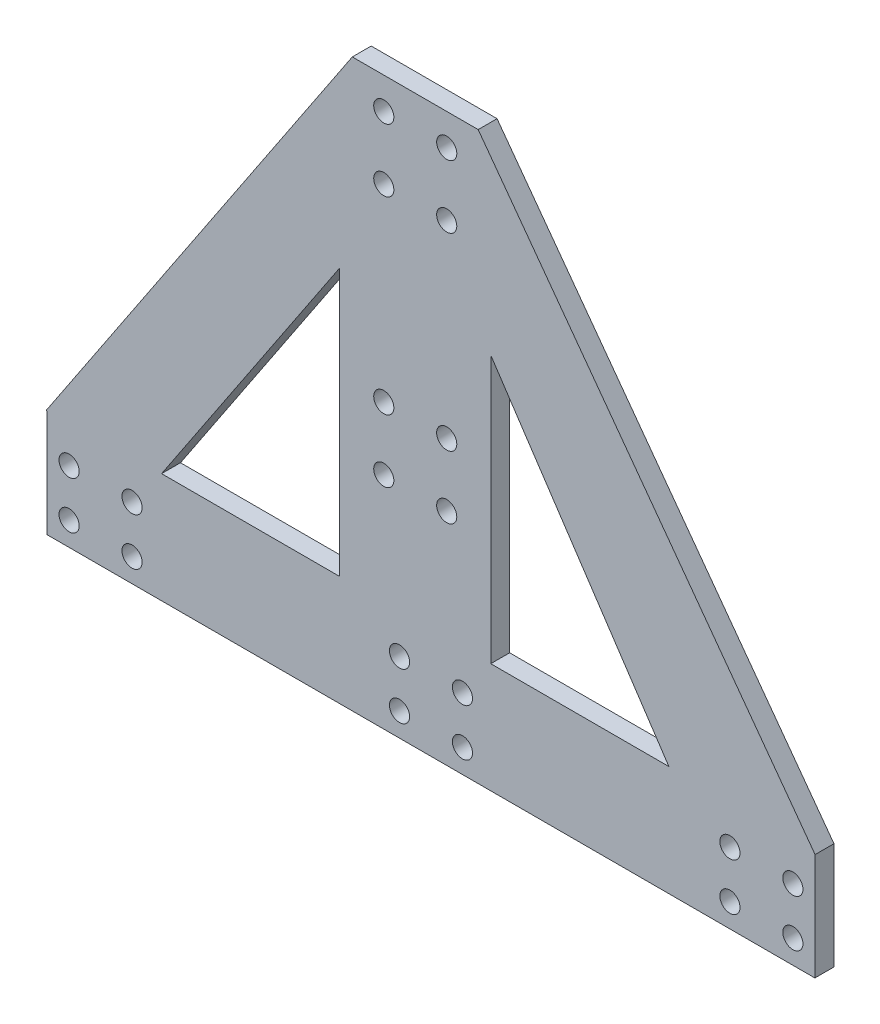
SolidWorks part; units mm, degrees
ref_plane "前视基准面" through (0, 0, 0) normal (0, 0, 1) x (1, 0, 0)
ref_plane "上视基准面" through (0, 0, 0) normal (0, 1, 0) x (1, 0, 0)
ref_plane "右视基准面" through (0, 0, 0) normal (1, 0, 0) x (0, 0, -1)
other "Configuration Table"
sketch "草图1" plane through (0, 0, 0) normal (0, 0, 1) x (1, 0, 0)
  line L0 (0, 0) -> (20, 0)
  line L1 (20, 0) -> (75, -75)
  line L2 (75, -75) -> (75, -90)
  line L3 (75, -90) -> (-50, -90)
  line L4 (-50, -90) -> (-50, -75)
  line L5 (-50, -75) -> (0, 0)
  line L6 (10, 0) -> (10, -90) construction
  dimension "D1" = 15
  dimension "D2" = 20
  dimension "D3" = 15
  dimension "D4" = 90
  dimension "D5" = 125
  dimension "D6" = 60
extrude "凸台-拉伸1" add sketch "草图1" along normal blind 3
sketch "草图2" plane through (0, 0, 3) normal (0, 0, 1) x (1, 0, 0)
  line L0 (10, 0) -> (10, -90) construction
  line L1 (20, 0) -> (0, 0) construction
  line L2 (-50, -90) -> (75, -90) construction
  line L3 (10, -10) -> (-19.8035, -10) construction
  line L4 (-50, -82.5) -> (75, -82.5) construction
  line L5 (-50, -75) -> (-50, -90) construction
  line L6 (75, -90) -> (75, -75) construction
  line L7 (-40, -82.5) -> (-40, -90) construction
  line L8 (12.5, -90) -> (12.5, -82.5) construction
  line L9 (65, -82.5) -> (65, -90) construction
  line L10 (-2, -30.0416) -> (-2, -72.5)
  line L11 (-2, -72.5) -> (-30.3056, -72.5)
  line L12 (-30.3056, -72.5) -> (-2, -30.0416)
  line L13 (0, 0) -> (-50, -75) construction
  line L14 (22, -72.5) -> (50.3056, -72.5)
  line L15 (50.3056, -72.5) -> (22, -30.0416)
  line L16 (22, -30.0416) -> (22, -72.5)
  line L17 (75, -90) -> (75, -73)
  line L18 (-48.5, -90) -> (-50, -90)
  line L19 (-48.5, -90) -> (-48.5, -73)
  line L20 (-48.5, -73) -> (-50, -73)
  line L21 (-50, -90) -> (-50, -73)
  line L22 (73.5, -73) -> (75, -73)
  line L23 (73.5, -90) -> (73.5, -73)
  line L24 (73.5, -90) -> (75, -90)
  line L25 (10, -30) -> (-38.6049, -30) construction
  circle A0 centre (5, -5) radius 1.6
  circle A1 centre (15, -5) radius 1.6
  circle A2 centre (15, -15) radius 1.6
  circle A3 centre (5, -15) radius 1.6
  circle A4 centre (-45, -86.25) radius 1.6
  circle A5 centre (-45, -78.75) radius 1.6
  circle A6 centre (-35, -86.25) radius 1.6
  circle A7 centre (-35, -78.75) radius 1.6
  circle A8 centre (60, -78.75) radius 1.6
  circle A9 centre (60, -86.25) radius 1.6
  circle A10 centre (70, -78.75) radius 1.6
  circle A11 centre (70, -86.25) radius 1.6
  circle A12 centre (7.5, -86.25) radius 1.6
  circle A13 centre (17.5, -86.25) radius 1.6
  circle A14 centre (17.5, -78.75) radius 1.6
  circle A15 centre (7.5, -78.75) radius 1.6
  circle A16 centre (5, -45) radius 1.6
  circle A17 centre (15, -45) radius 1.6
  circle A18 centre (15, -55) radius 1.6
  circle A19 centre (5, -55) radius 1.6
  dimension "D1" = 10
  dimension "D3" = 3.2
  dimension "D5" = 5
  dimension "D7" = 3.2
  dimension "D12" = 3.2
  dimension "D2" = 5
  dimension "D4" = 5
  dimension "D6" = 10
  dimension "D8" = 3.75
  dimension "D9" = 12
  dimension "D10" = 10
  dimension "D11" = 15
  dimension "D13" = 5
  dimension "D14" = 3.75
  dimension "D15" = 1.5
  dimension "D16" = 17
  dimension "D17" = 20
extrude "切除-拉伸1" cut sketch "草图2" against normal through all
